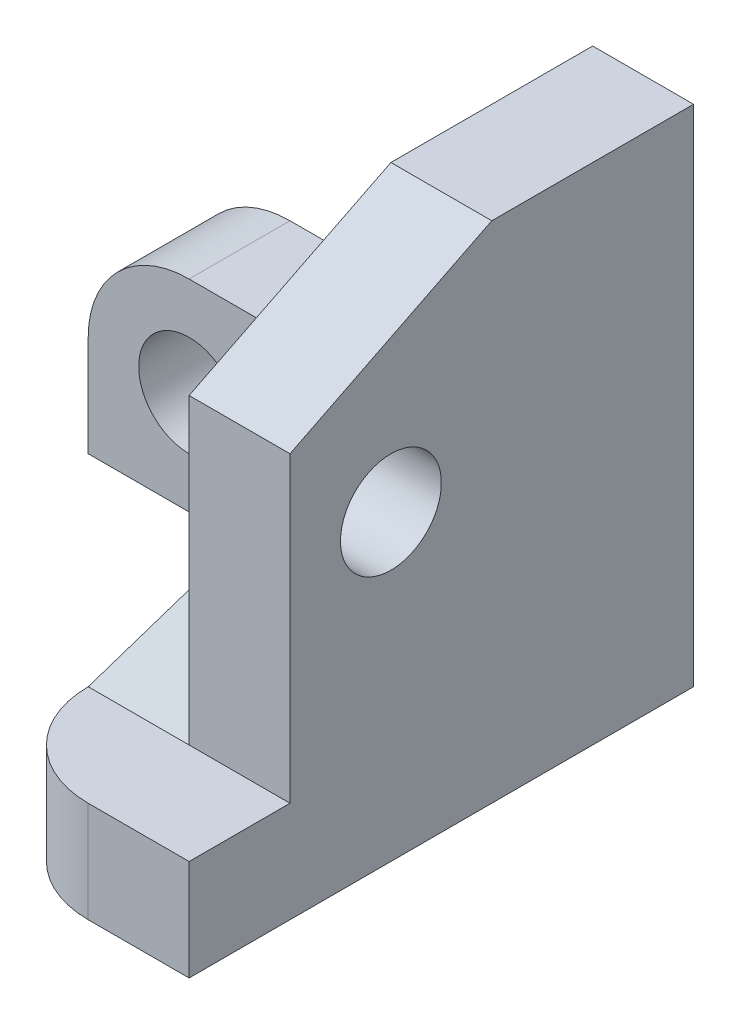
SolidWorks part; units mm, degrees
ref_plane "Płaszczyzna przednia" through (0, 0, 0) normal (0, 0, 1) x (1, 0, 0)
ref_plane "Płaszczyzna górna" through (0, 0, 0) normal (0, 1, 0) x (1, 0, 0)
ref_plane "Płaszczyzna prawa" through (0, 0, 0) normal (1, 0, 0) x (0, 0, -1)
sketch "Szkic1" plane through (0, 0, 0) normal (0, 0, 1) x (1, 0, 0)
  line L0 (0, 0) -> (40, 0)
  line L1 (40, 0) -> (40, 20)
  line L2 (40, 20) -> (10, 20)
  line L3 (0, 10) -> (0, 0)
  arc A0 (10, 20) -> (0, 10) centre (10, 10) ccw
  circle A1 centre (10, 10) radius 5
  dimension "D1" = 10
  dimension "D4" = 10
  dimension "D2" = 10
  dimension "D3" = 10
  dimension "D5" = 20
  dimension "D6" = 40
extrude "Dodanie-wyciągnięcie3" add sketch "Szkic1" along normal blind 10
sketch "Szkic2" plane through (0, 0, 0) normal (0, 1, 0) x (1, 0, 0)
  line L0 (40, 0) -> (40, -10)
  line L1 (40, 0) -> (50, 0)
  line L2 (50, 0) -> (50, -40)
  line L3 (50, -40) -> (40, -40)
  line L4 (40, -40) -> (40, -10)
  dimension "D1" = 10
  dimension "D2" = 40
extrude "Dodanie-wyciągnięcie4" add sketch "Szkic2" along normal blind 50
sketch "Szkic3" plane through (40, 0, 0) normal (-1, 0, 0) x (0, 0, 1)
  line L1 (40, 50) -> (40, 0) construction
  line L2 (40, 40) -> (20, 50)
  line L3 (0, 50) -> (40, 50) construction
  line L9 (40, 50) -> (20, 50)
  line L10 (40, 40) -> (40, 50)
  dimension "D1" = 10
  dimension "D2" = 20
extrude "Wytnij-wyciągnięcie1" cut sketch "Szkic3" against normal blind 40
sketch "Szkic5" plane through (40, 0, 0) normal (-1, 0, 0) x (0, 0, 1)
  circle A0 centre (30, 30) radius 5
  dimension "D1" = 10
  dimension "D2" = 10
  dimension "D3" = 10
extrude "Wytnij-wyciągnięcie2" cut sketch "Szkic5" against normal blind 40
sketch "Szkic6" plane through (40, 0, 0) normal (-1, 0, 0) x (0, 0, 1)
  line L0 (10, 0) -> (10, 20)
  line L1 (10, 20) -> (40, 10)
  line L2 (40, 40) -> (40, 0) construction
  line L3 (40, 10) -> (40, 0)
  line L4 (10, 0) -> (40, 0) construction
  line L5 (40, 0) -> (10, 0)
  dimension "D1" = 10
extrude "Dodanie-wyciągnięcie5" add sketch "Szkic6" along normal blind 10
sketch "Szkic7" plane through (0, 0, 0) normal (0, 1, 0) x (1, 0, 0)
  line L0 (50, -40) -> (30, -40)
  line L1 (40, -50) -> (50, -50)
  line L2 (50, -50) -> (50, -40)
  arc A0 (30, -40) -> (40, -50) centre (40, -40) ccw
  dimension "D1" = 10
extrude "Dodanie-wyciągnięcie6" add sketch "Szkic7" along normal blind 10
